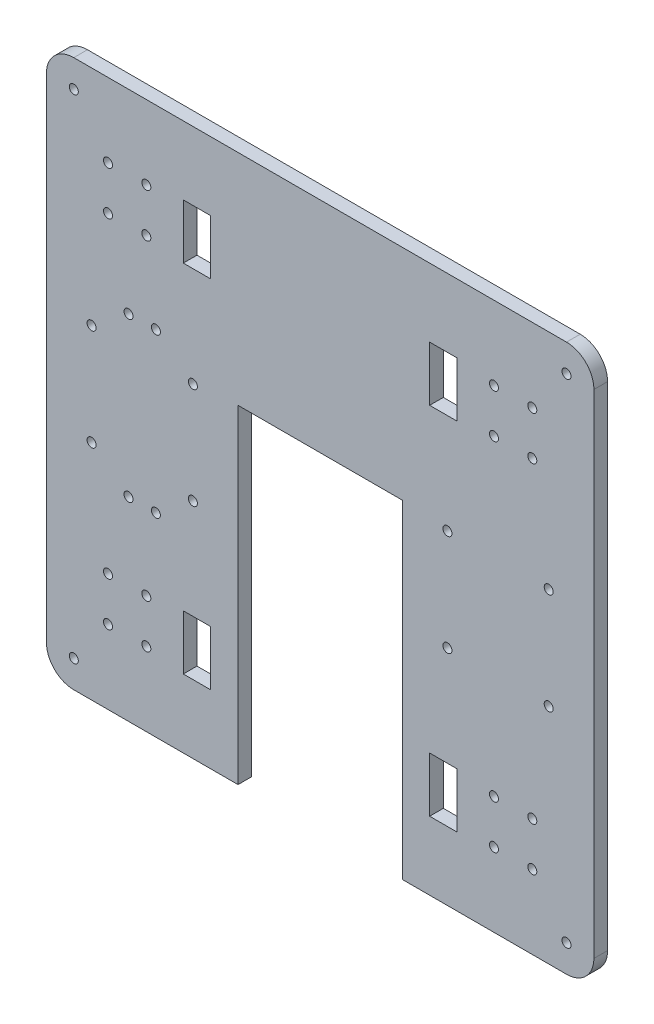
SolidWorks part; units mm, degrees
ref_plane "前视基准面" through (0, 0, 0) normal (0, 0, 1) x (1, 0, 0)
ref_plane "上视基准面" through (0, 0, 0) normal (0, 1, 0) x (1, 0, 0)
ref_plane "右视基准面" through (0, 0, 0) normal (1, 0, 0) x (0, 0, -1)
sketch "Model" plane through (0, 0, 0) normal (0, 0, 1) x (1, 0, 0)
  line L0 (197.7121, 317.514) -> (377.7121, 317.514)
  line L1 (387.7121, 307.514) -> (387.7121, 127.514)
  line L2 (377.7121, 117.514) -> (317.7121, 117.514)
  line L3 (317.7121, 117.514) -> (317.7121, 237.514)
  line L4 (317.7121, 237.514) -> (257.7121, 237.514)
  line L5 (257.7121, 237.514) -> (257.7121, 117.514)
  line L6 (257.7121, 117.514) -> (197.7121, 117.514)
  line L7 (187.7121, 127.514) -> (187.7121, 307.514)
  line L8 (247.7121, 142.514) -> (242.7121, 142.514)
  line L9 (247.7121, 142.514) -> (247.7121, 162.514)
  line L10 (247.7121, 162.514) -> (237.7121, 162.514)
  line L11 (237.7121, 162.514) -> (237.7121, 142.514)
  line L12 (237.7121, 142.514) -> (242.7121, 142.514)
  line L13 (327.7121, 142.514) -> (332.7121, 142.514)
  line L14 (327.7121, 142.514) -> (327.7121, 162.514)
  line L15 (327.7121, 162.514) -> (337.7121, 162.514)
  line L16 (337.7121, 162.514) -> (337.7121, 142.514)
  line L17 (337.7121, 142.514) -> (332.7121, 142.514)
  line L18 (247.7121, 292.514) -> (242.7121, 292.514)
  line L19 (247.7121, 292.514) -> (247.7121, 272.514)
  line L20 (247.7121, 272.514) -> (237.7121, 272.514)
  line L21 (237.7121, 272.514) -> (237.7121, 292.514)
  line L22 (237.7121, 292.514) -> (242.7121, 292.514)
  line L23 (327.7121, 292.514) -> (332.7121, 292.514)
  line L24 (327.7121, 292.514) -> (327.7121, 272.514)
  line L25 (327.7121, 272.514) -> (337.7121, 272.514)
  line L26 (337.7121, 272.514) -> (337.7121, 292.514)
  line L27 (337.7121, 292.514) -> (332.7121, 292.514)
  arc A0 (197.7121, 317.514) -> (187.7121, 307.514) centre (197.7121, 307.514) ccw
  arc A1 (377.7121, 117.514) -> (387.7121, 127.514) centre (377.7121, 127.514) ccw
  arc A2 (387.7121, 307.514) -> (377.7121, 317.514) centre (377.7121, 307.514) ccw
  arc A3 (187.7121, 127.514) -> (197.7121, 117.514) centre (197.7121, 127.514) ccw
  circle A4 centre (204.2121, 236.014) radius 1.65
  circle A5 centre (197.7121, 127.514) radius 1.65
  circle A6 centre (377.7121, 127.514) radius 1.65
  circle A7 centre (197.7121, 307.514) radius 1.65
  circle A8 centre (377.7121, 307.514) radius 1.65
  circle A9 centre (241.2121, 236.014) radius 1.65
  circle A10 centre (204.2121, 199.014) radius 1.65
  circle A11 centre (241.2121, 199.014) radius 1.65
  circle A12 centre (371.2121, 236.014) radius 1.65
  circle A13 centre (334.2121, 236.014) radius 1.65
  circle A14 centre (371.2121, 199.014) radius 1.65
  circle A15 centre (334.2121, 199.014) radius 1.65
  circle A16 centre (210.2121, 290.514) radius 1.65
  circle A17 centre (224.2121, 290.514) radius 1.65
  circle A18 centre (210.2121, 274.514) radius 1.65
  circle A19 centre (224.2121, 274.514) radius 1.65
  circle A20 centre (210.2121, 144.514) radius 1.65
  circle A21 centre (210.2121, 160.514) radius 1.65
  circle A22 centre (365.2121, 290.514) radius 1.65
  circle A23 centre (351.2121, 290.514) radius 1.65
  circle A24 centre (365.2121, 274.514) radius 1.65
  circle A25 centre (351.2121, 274.514) radius 1.65
  circle A26 centre (365.2121, 144.514) radius 1.65
  circle A27 centre (365.2121, 160.514) radius 1.65
  circle A28 centre (224.2121, 144.514) radius 1.65
  circle A29 centre (224.2121, 160.514) radius 1.65
  circle A30 centre (351.2121, 144.514) radius 1.65
  circle A31 centre (351.2121, 160.514) radius 1.65
  circle A32 centre (227.7121, 246.514) radius 1.65
  circle A33 centre (217.7121, 246.4422) radius 1.65
  circle A34 centre (227.7121, 188.514) radius 1.65
  circle A35 centre (217.7121, 188.5859) radius 1.65
extrude "凸台-拉伸1" add sketch "Model" along normal blind 5
